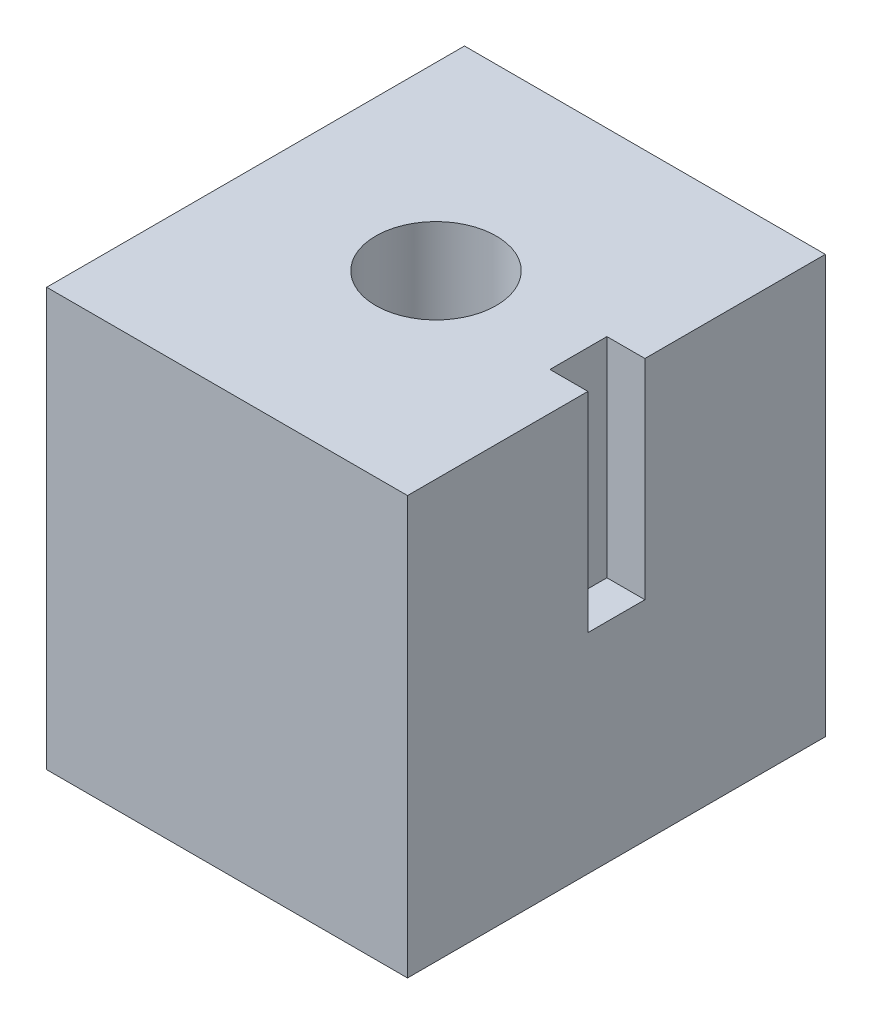
SolidWorks part; units mm, degrees
ref_plane "Front Plane" through (0, 0, 0) normal (0, 0, 1) x (1, 0, 0)
ref_plane "Top Plane" through (0, 0, 0) normal (0, 1, 0) x (1, 0, 0)
ref_plane "Right Plane" through (0, 0, 0) normal (1, 0, 0) x (0, 0, -1)
sketch "Sketch1" plane through (0, 0, 0) normal (0, 1, 0) x (1, 0, 0)
  line L1 (-9.5, -11) -> (9.5, -11)
  line L2 (-9.5, -11) -> (-9.5, 11)
  line L3 (-9.5, 11) -> (9.5, 11)
  line L4 (9.5, -11) -> (9.5, 11)
  line L5 (-9.5, -11) -> (9.5, 11) construction
  line L6 (-9.5, 11) -> (9.5, -11) construction
  point P0 (0, 0)
  dimension "D1" = 19
  dimension "D2" = 22
extrude "Boss-Extrude1" add sketch "Sketch1" against normal blind 22
sketch "Sketch2" plane through (0, 0, 0) normal (0, 1, 0) x (1, 0, 0)
  circle A0 centre (0, 0) radius 3.175
  dimension "D1" = 6.35
extrude "Cut-Extrude1" cut sketch "Sketch2" against normal up to surface (22 mm away) up to face at (0, -22, 0)
sketch "Sketch3" plane through (0, -22, 0) normal (0, -1, 0) x (1, 0, 0)
  circle A0 centre (0, 0) radius 7.5
  dimension "D1" = 15
extrude "Cut-Extrude2" cut sketch "Sketch3" against normal blind 5.5
sketch "Sketch4" plane through (0, 0, 0) normal (0, 1, 0) x (1, 0, 0)
  line L0 (-9.5, 0) -> (9.5, 0) construction
  line L1 (-9.5, 11) -> (-9.5, -11) construction
  line L2 (9.5, -11) -> (9.5, 11) construction
  line L3 (0, 11) -> (0, -11) construction
  line L4 (9.5, 1.5) -> (7.5, 1.5)
  line L5 (9.5, 1.5) -> (9.5, -1.5)
  line L6 (9.5, -1.5) -> (7.5, -1.5)
  line L7 (7.5, 1.5) -> (7.5, -1.5)
  line L8 (9.5, 1.5) -> (7.5, -1.5) construction
  line L9 (9.5, -1.5) -> (7.5, 1.5) construction
  line L10 (9.5, 11) -> (-9.5, 11) construction
  line L11 (-9.5, -11) -> (9.5, -11) construction
  point P6 (8.5, 0)
  dimension "D1" = 3
  dimension "D2" = 2
extrude "Cut-Extrude5" cut sketch "Sketch4" against normal blind 11
